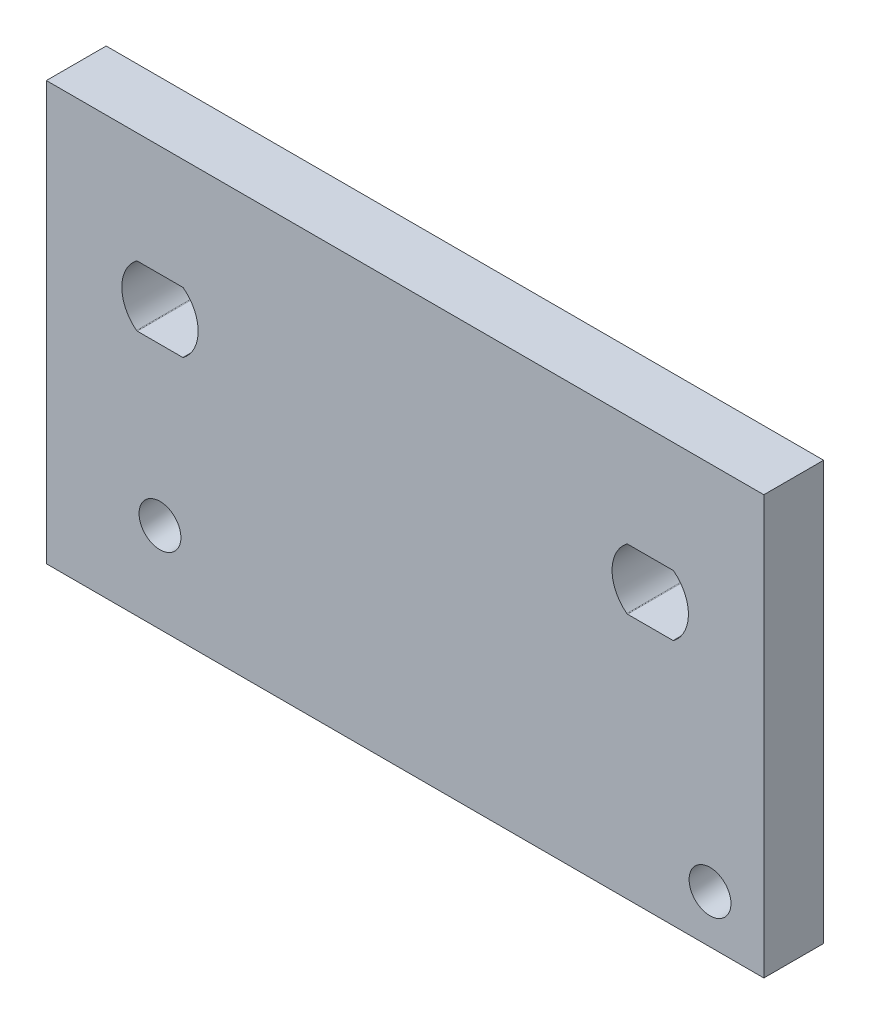
SolidWorks part; units mm, degrees
ref_plane "Front Plane" through (0, 0, 0) normal (0, 0, 1) x (1, 0, 0)
ref_plane "Top Plane" through (0, 0, 0) normal (0, 1, 0) x (1, 0, 0)
ref_plane "Right Plane" through (0, 0, 0) normal (1, 0, 0) x (0, 0, -1)
sketch "Sketch1" plane through (0, 0, 0) normal (0, 0, 1) x (1, 0, 0)
  line L1 (-70, 35) -> (70, 35)
  line L2 (-70, 35) -> (-70, -35)
  line L3 (-70, -35) -> (70, -35)
  line L4 (70, 35) -> (70, -35)
  line L5 (-70, 35) -> (70, -35) construction
  line L6 (-70, -35) -> (70, 35) construction
  point P0 (0, 0)
  dimension "D1" = 140
  dimension "D2" = 70
extrude "Boss-Extrude1" add sketch "Sketch1" along normal blind 10
sketch "Sketch2" plane through (0, 0, 0) normal (0, 0, -1) x (-1, 0, 0)
  line L2 (-44.7993, 6.2961) -> (-37.2007, 6.2961) construction
  line L3 (-37.2007, 16.4561) -> (-44.7993, 16.4561) construction
  line L4 (0, 0) -> (0, -35) construction
  line L5 (70, -35) -> (-70, -35) construction
  line L6 (-44.7993, 6.2961) -> (-37.2007, 6.2961)
  line L7 (-37.2007, 16.4561) -> (-44.7993, 16.4561)
  line L8 (37.2007, 16.4561) -> (44.7993, 16.4561)
  line L9 (44.7993, 6.2961) -> (37.2007, 6.2961)
  arc A2 (-37.0758, 6.339) -> (-37.0758, 16.4132) centre (-41, 11.3761) ccw construction
  arc A3 (-44.9242, 16.4132) -> (-44.9242, 6.339) centre (-41, 11.3761) ccw construction
  arc A4 (37.0758, 16.4132) -> (37.2007, 16.4561) centre (37.2007, 16.2529) cw
  arc A5 (37.2007, 6.2961) -> (37.0758, 6.339) centre (37.2007, 6.4993) cw
  arc A6 (-37.0758, 6.339) -> (-37.0758, 16.4132) centre (-41, 11.3761) ccw
  arc A7 (-44.9242, 16.4132) -> (-44.9242, 6.339) centre (-41, 11.3761) ccw
  arc A8 (-44.7993, 16.4561) -> (-44.9242, 16.4132) centre (-44.7993, 16.2529) ccw construction
  arc A9 (-44.9242, 6.339) -> (-44.7993, 6.2961) centre (-44.7993, 6.4993) ccw construction
  arc A10 (-37.2007, 6.2961) -> (-37.0758, 6.339) centre (-37.2007, 6.4993) ccw construction
  arc A11 (-37.0758, 16.4132) -> (-37.2007, 16.4561) centre (-37.2007, 16.2529) ccw construction
  arc A12 (-44.7993, 16.4561) -> (-44.9242, 16.4132) centre (-44.7993, 16.2529) ccw
  arc A13 (-44.9242, 6.339) -> (-44.7993, 6.2961) centre (-44.7993, 6.4993) ccw
  arc A14 (-37.2007, 6.2961) -> (-37.0758, 6.339) centre (-37.2007, 6.4993) ccw
  arc A15 (-37.0758, 16.4132) -> (-37.2007, 16.4561) centre (-37.2007, 16.2529) ccw
  arc A16 (44.9242, 6.339) -> (44.7993, 6.2961) centre (44.7993, 6.4993) cw
  arc A17 (44.7993, 16.4561) -> (44.9242, 16.4132) centre (44.7993, 16.2529) cw
  arc A18 (44.9242, 16.4132) -> (44.9242, 6.339) centre (41, 11.3761) cw
  arc A19 (37.0758, 6.339) -> (37.0758, 16.4132) centre (41, 11.3761) cw
extrude "Cut-Extrude1" cut sketch "Sketch2" against normal through all
ref_plane "Plane1" through (0, -0.6185, 11.8019) normal (0, -0.0523, 0.9986) x (1, 0, 0)
sketch "Sketch3" plane through (70, 0, 0) normal (1, 0, 0) x (0, 0, -1)
  line L4 (0, -35) -> (0, 35)
  line L5 (0, 35) -> (-10, 35)
  line L6 (-10, 35) -> (-10, -35)
  line L7 (-10, -35) -> (0, -35)
  line L8 (0, -35) -> (0, 35)
  line L9 (0, 35) -> (-10, 35)
  line L10 (-10, 35) -> (-10, -35)
  line L11 (-10, -35) -> (0, -35)
  dimension "D1" = 0
extrude "Cut-Extrude2" cut sketch "Sketch3" against normal blind 10
sketch "Sketch4" plane through (-70, 0, 0) normal (-1, 0, 0) x (0, 0, 1)
  line L4 (0, 35) -> (0, -35)
  line L5 (0, -35) -> (10, -35)
  line L6 (10, -35) -> (10, 35)
  line L7 (10, 35) -> (0, 35)
  line L8 (0, 35) -> (0, -35)
  line L9 (0, -35) -> (10, -35)
  line L10 (10, -35) -> (10, 35)
  line L11 (10, 35) -> (0, 35)
  dimension "D1" = 0
extrude "Cut-Extrude3" cut sketch "Sketch4" against normal blind 10
ref_plane "Plane2" through (0, -0.8662, 12.3869) normal (0, -0.0698, 0.9976) x (1, 0, 0)
sketch "Sketch5" plane through (0, -0.8662, 12.3869) normal (0, -0.0698, 0.9976) x (1, 0, 0)
  line L0 (60, 35.6123) -> (60, -34.2172) construction
  line L1 (-60, -34.2172) -> (60, -34.2172) construction
  line L2 (-60, -34.2172) -> (-60, 35.6123) construction
  circle A0 centre (51, -26.2172) radius 3.5
  circle A1 centre (-41, -19.2172) radius 3.5
  dimension "D1" = 7
  dimension "D2" = 9
  dimension "D3" = 8
  dimension "D4" = 7
  dimension "D5" = 15
  dimension "D6" = 19
extrude "Cut-Extrude4" cut sketch "Sketch5" against normal through all
